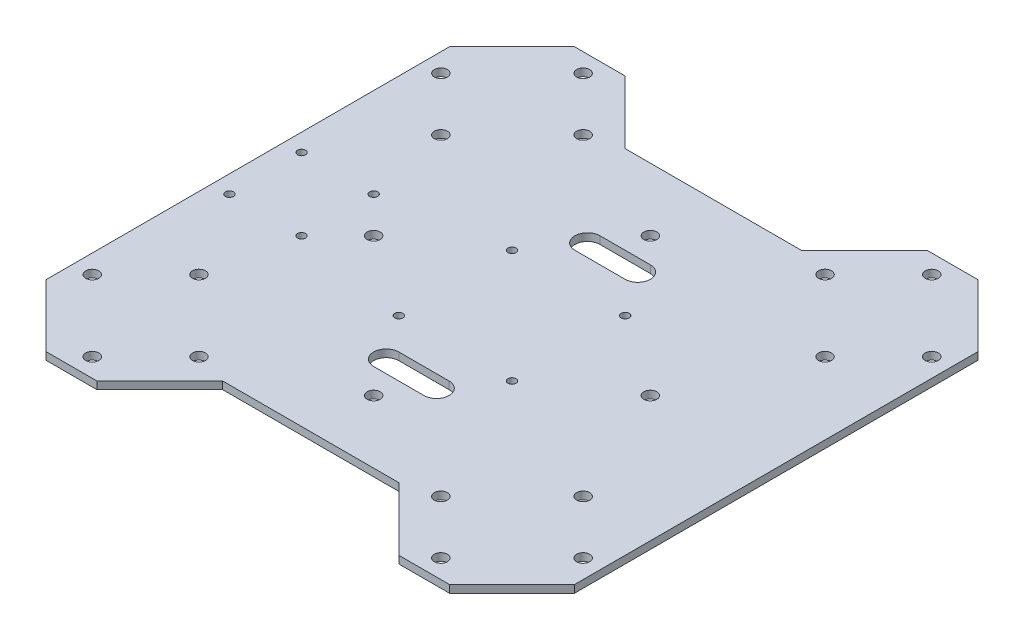
SolidWorks part; units mm, degrees
material "3k Carbon Fiber"
ref_plane "Front Plane" through (0, 0, 0) normal (0, 0, 1) x (1, 0, 0)
ref_plane "Top Plane" through (0, 0, 0) normal (0, 1, 0) x (1, 0, 0)
ref_plane "Right Plane" through (0, 0, 0) normal (1, 0, 0) x (0, 0, -1)
sketch "Sketch1" plane through (0, 0, 0) normal (0, 1, 0) x (1, 0, 0)
  line L0 (-59.3167, 108.2255) -> (101.1858, 108.2255)
  line L1 (101.1858, 108.2255) -> (125.9346, 83.4768)
  line L2 (125.9346, 83.4768) -> (125.9346, -77.0258)
  line L3 (125.9346, -77.0258) -> (101.1858, -101.7745)
  line L4 (101.1858, -101.7745) -> (-59.3167, -101.7745)
  line L5 (-59.3167, -101.7745) -> (-84.0654, -77.0258)
  line L6 (-84.0654, -77.0258) -> (-84.0654, 83.4768)
  line L7 (-84.0654, 83.4768) -> (-59.3167, 108.2255)
  dimension "D1" = 210
  dimension "D2" = 135
  dimension "D3" = 135
  dimension "D4" = 35
extrude "Boss-Extrude1" add sketch "Sketch1" along normal blind 3
sketch "Sketch2" plane through (0, 3, 0) normal (0, 1, 0) x (1, 0, 0)
  line L0 (-84.0654, -77.0258) -> (-45.1746, -38.1349)
  line L1 (-45.1746, -38.1349) -> (-20.4258, -62.8836)
  line L2 (-20.4258, -62.8836) -> (-59.3167, -101.7745)
  line L3 (125.9346, -77.0258) -> (93.8808, -37.1048)
  line L4 (93.8808, -37.1048) -> (66.7511, -58.8881)
  line L5 (66.7511, -58.8881) -> (101.1858, -101.7745)
  line L6 (101.1858, 108.2255) -> (62.1611, 69.9555)
  line L7 (62.1611, 69.9555) -> (86.6658, 44.9675)
  line L8 (86.6658, 44.9675) -> (125.9346, 83.4768)
  line L9 (-59.3167, 108.2255) -> (-24.1003, 65.9786)
  line L10 (-24.1003, 65.9786) -> (-50.8746, 43.6598)
  line L11 (-50.8746, 43.6598) -> (-84.0654, 83.4768)
  line L12 (-84.0654, -77.0258) -> (-59.3167, -101.7745)
  line L13 (101.1858, -101.7745) -> (125.9346, -77.0258)
  line L14 (101.1858, 108.2255) -> (125.9346, 83.4768)
  line L15 (-84.0654, 83.4768) -> (-59.3167, 108.2255)
  dimension "D1" = 55
  dimension "D2" = 90
  dimension "D3" = 55
  dimension "D4" = 90
  dimension "D5" = 55
  dimension "D6" = 90
  dimension "D7" = 90
  dimension "D8" = 55
  dimension "D9" = 90
extrude "Boss-Extrude2" add sketch "Sketch2" against normal blind 2
sketch "Sketch3" plane through (0, 3, 0) normal (0, 1, 0) x (1, 0, 0)
  line L0 (20.9346, 108.2255) -> (20.9346, -101.7745) construction
  line L1 (101.1858, 108.2255) -> (-59.3167, 108.2255) construction
  line L2 (-59.3167, -101.7745) -> (101.1858, -101.7745) construction
  line L3 (-84.0654, 3.2255) -> (125.9346, 3.2255) construction
  line L4 (-84.0654, 83.4768) -> (-84.0654, -77.0258) construction
  line L5 (125.9346, -77.0258) -> (125.9346, 83.4768) construction
  line L10 (-41.2855, 65.4455) -> (-71.6911, 95.8511) construction
  line L11 (-50.195, 98.9624) -> (-48.3565, 100.8009) construction
  line L12 (-48.3565, 100.8009) -> (-27.1433, 79.5877) construction
  line L13 (-27.1433, 79.5877) -> (-55.4276, 51.3034) construction
  line L14 (-55.4276, 51.3034) -> (-76.6408, 72.5166) construction
  line L23 (-59.3167, 108.2255) -> (-84.0654, 83.4768) construction
  circle A9 centre (-27.1433, 79.5877) radius 2.6
  circle A10 centre (-55.4276, 51.3034) radius 2.6
  circle A11 centre (-76.6408, 72.5166) radius 2.6
  circle A16 centre (-48.3565, 100.8009) radius 2.6
  circle A18 centre (118.51, 72.5166) radius 2.6
  circle A19 centre (97.2968, 51.3034) radius 2.6
  circle A20 centre (69.0125, 79.5877) radius 2.6
  circle A21 centre (90.2257, 100.8009) radius 2.6
  circle A22 centre (97.2968, -44.8524) radius 2.6
  circle A23 centre (118.51, -66.0656) radius 2.6
  circle A24 centre (90.2257, -94.3499) radius 2.6
  circle A25 centre (69.0125, -73.1367) radius 2.6
  circle A26 centre (-27.1433, -73.1367) radius 2.6
  circle A27 centre (-55.4276, -44.8524) radius 2.6
  circle A28 centre (-76.6408, -66.0656) radius 2.6
  circle A29 centre (-48.3565, -94.3499) radius 2.6
  dimension "D11" = 43
  dimension "D12" = 2.6
  dimension "D13" = 30
  dimension "D14" = 40
  dimension "D15" = 30
sketch "Sketch7" plane through (0, 3, 0) normal (0, 1, 0) x (1, 0, 0)
  line L0 (20.9346, 108.2255) -> (20.9346, -101.7745)
  line L1 (101.1858, 108.2255) -> (-59.3167, 108.2255) construction
  line L2 (-59.3167, -101.7745) -> (101.1858, -101.7745) construction
  line L4 (-1.5654, -19.2745) -> (43.4346, -19.2745)
  line L5 (-1.5654, -19.2745) -> (-1.5654, 25.7255)
  line L6 (-1.5654, 25.7255) -> (43.4346, 25.7255)
  line L7 (43.4346, -19.2745) -> (43.4346, 25.7255)
  line L8 (-1.5654, -19.2745) -> (43.4346, 25.7255) construction
  line L9 (-1.5654, 25.7255) -> (43.4346, -19.2745) construction
  circle A0 centre (43.4346, 25.7255) radius 1.6
  circle A1 centre (-1.5654, 25.7255) radius 1.6
  circle A2 centre (-1.5654, -19.2745) radius 1.6
  circle A3 centre (43.4346, -19.2745) radius 1.6
  point P6 (20.9346, 3.2255)
  dimension "D3" = 3.2
  dimension "D1" = 45
  dimension "D2" = 45
extrude "Cut-Extrude4" cut sketch "Sketch7" against normal through all contours L4 A2 L5 | L5 A2 L4 | L7 A3 L4 | L4 A3 L7 | L7 A0 L6 | L6 A0 L7 | L5 A1 L6 | L6 A1 L5
extrude "Cut-Extrude5" cut sketch "Sketch3" against normal through all contours A27 | A28 | A29 | A26 | A11 | A10 | A16 | A9 | A20 | A21 | A18 | A19 | A25 | A22 | A23 | A24
sketch "Sketch9" plane through (0, 3, 0) normal (0, 1, 0) x (1, 0, 0)
  line L0 (20.9346, 108.2255) -> (20.9346, 83.2255) construction
  line L1 (101.1858, 108.2255) -> (-59.3167, 108.2255) construction
  line L2 (-14.0654, 83.2255) -> (55.9346, 83.2255)
  line L3 (-14.0654, 83.2255) -> (-39.0654, 108.2255)
  line L4 (55.9346, 83.2255) -> (80.9346, 108.2255)
  line L5 (-39.0654, 108.2255) -> (80.9346, 108.2255)
  line L6 (125.9346, 3.2255) -> (-84.0654, 3.2255) construction
  line L7 (125.9346, -77.0258) -> (125.9346, 83.4768) construction
  line L8 (-84.0654, 83.4768) -> (-84.0654, -77.0258) construction
  line L9 (-14.0654, -76.7745) -> (-39.0654, -101.7745)
  line L10 (-14.0654, -76.7745) -> (55.9346, -76.7745)
  line L11 (55.9346, -76.7745) -> (80.9346, -101.7745)
  line L12 (-39.0654, -101.7745) -> (80.9346, -101.7745)
  point P7 (20.9346, 83.2255)
  dimension "D1" = 70
  dimension "D2" = 25
  dimension "D3" = 135
extrude "Cut-Extrude7" cut sketch "Sketch9" against normal through all
sketch "Sketch11" plane through (0, 3, 0) normal (0, 1, 0) x (1, 0, 0)
  line L0 (-84.0654, 3.2255) -> (-77.0654, 3.2255) construction
  line L1 (-84.0654, 83.4768) -> (-84.0654, -77.0258) construction
  line L2 (-77.0654, -11.1145) -> (-77.0654, 17.5655) construction
  line L3 (-77.0654, 17.5655) -> (-48.3854, 17.5655) construction
  circle A0 centre (-77.0654, 17.5655) radius 1.6
  circle A1 centre (-77.0654, -11.1145) radius 1.6
  circle A2 centre (-48.3854, 17.5655) radius 1.6
  circle A3 centre (-48.3854, -11.1145) radius 1.6
  point P7 (-77.0654, 3.2255)
  dimension "D3" = 3.2
  dimension "D1" = 7
  dimension "D2" = 28.68
  dimension "D4" = 28.68
extrude "Cut-Extrude10" cut sketch "Sketch11" against normal blind 10 contours A3 | A2 | A0 | A1
sketch "Sketch12" plane through (0, 3, 0) normal (0, 1, 0) x (1, 0, 0)
  line L0 (20.9346, 83.2255) -> (20.9346, -76.7745) construction
  line L1 (-14.0654, 83.2255) -> (55.9346, 83.2255) construction
  line L2 (55.9346, -76.7745) -> (-14.0654, -76.7745) construction
  line L3 (-84.0654, 3.2255) -> (125.9346, 3.2255) construction
  line L4 (-84.0654, 83.4768) -> (-84.0654, -77.0258) construction
  line L5 (125.9346, -77.0258) -> (125.9346, 83.4768) construction
  line L7 (20.9346, -32.1298) -> (56.2899, 3.2255)
  line L8 (20.9346, -32.1298) -> (-14.4208, 3.2255)
  line L9 (-14.4208, 3.2255) -> (20.9346, 38.5808)
  line L10 (56.2899, 3.2255) -> (20.9346, 38.5808)
  line L11 (-4.0654, -21.7745) -> (45.9346, 28.2255) construction
  line L12 (-4.0654, 28.2255) -> (45.9346, -21.7745) construction
  circle A0 centre (20.9346, 58.2255) radius 2.6
  circle A1 centre (-34.0654, 3.2255) radius 2.6
  circle A2 centre (20.9346, -51.7745) radius 2.6
  circle A3 centre (75.9346, 3.2255) radius 2.6
  point P12 (20.9346, 3.2255)
  dimension "D3" = 5.2
  dimension "D5" = 55
  dimension "D6" = 55
  dimension "D4" = 55
  dimension "D7" = 55
  dimension "D1" = 50
  dimension "D2" = 50
extrude "Cut-Extrude12" cut sketch "Sketch12" against normal blind 10 contours A1 | A2 | A3 | A0
sketch "Sketch13" plane through (0, 3, 0) normal (0, 1, 0) x (1, 0, 0)
  line L0 (20.9346, -76.7745) -> (20.9346, -36.7745) construction
  line L1 (20.9346, -36.7745) -> (0.1667, -36.7745) construction
  line L2 (10.9346, -41.7745) -> (30.9346, -41.7745)
  line L3 (10.9346, -31.7745) -> (30.9346, -31.7745)
  line L4 (55.9346, -76.7745) -> (-14.0654, -76.7745) construction
  line L5 (-84.0654, 3.2255) -> (125.9346, 3.2255) construction
  line L6 (-84.0654, 83.4768) -> (-84.0654, -77.0258) construction
  line L7 (125.9346, -77.0258) -> (125.9346, 83.4768) construction
  line L8 (10.9346, 38.2255) -> (30.9346, 38.2255)
  line L9 (10.9346, 48.2255) -> (30.9346, 48.2255)
  arc A0 (10.9346, -31.7745) -> (10.9346, -41.7745) centre (10.9346, -36.7745) ccw
  arc A1 (30.9346, -31.7745) -> (30.9346, -41.7745) centre (30.9346, -36.7745) cw
  arc A2 (10.9346, 38.2255) -> (10.9346, 48.2255) centre (10.9346, 43.2255) cw
  arc A3 (30.9346, 38.2255) -> (30.9346, 48.2255) centre (30.9346, 43.2255) ccw
  point P8 (20.9346, -31.7745)
  point P9 (20.9346, -41.7745)
  dimension "D2" = 5
  dimension "D1" = 40
  dimension "D3" = 20
extrude "Cut-Extrude13" cut sketch "Sketch13" against normal through all
